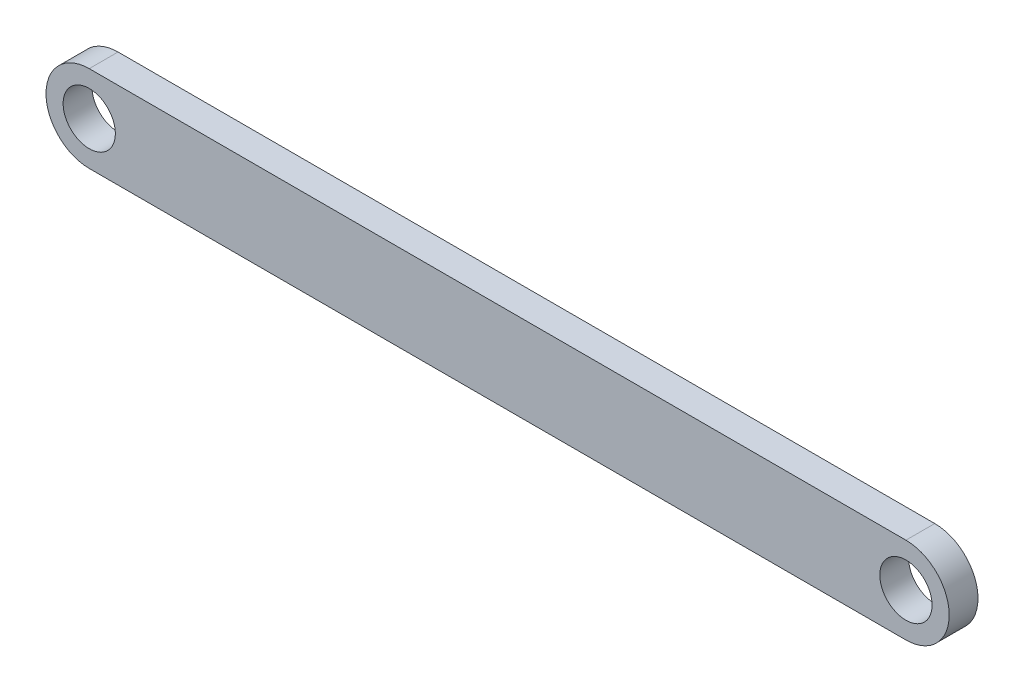
SolidWorks part; units mm, degrees
ref_plane "Front Plane" through (0, 0, 0) normal (0, 0, 1) x (1, 0, 0)
ref_plane "Top Plane" through (0, 0, 0) normal (0, 1, 0) x (1, 0, 0)
ref_plane "Right Plane" through (0, 0, 0) normal (1, 0, 0) x (0, 0, -1)
sketch "Sketch1" plane through (0, 0, 0) normal (0, 0, 1) x (1, 0, 0)
  line L0 (-27.2747, 0) -> (162.2122, 0) construction
  line L1 (0, 7.62) -> (143.9333, 7.62)
  line L2 (0, -7.62) -> (143.9333, -7.62)
  circle A0 centre (0, 0) radius 4.6037
  circle A1 centre (143.9333, 0) radius 4.6037
  arc A2 (0, 7.62) -> (0, -7.62) centre (0, 0) ccw
  arc A3 (143.9333, -7.62) -> (143.9333, 7.62) centre (143.9333, 0) ccw
  dimension "D1" = 9.2075
  dimension "D2" = 9.2075
  dimension "D4" = 15.24
  dimension "D5" = 15.24
  dimension "D3" = 143.9333
extrude "Boss-Extrude1" add sketch "Sketch1" along normal blind 5.08
